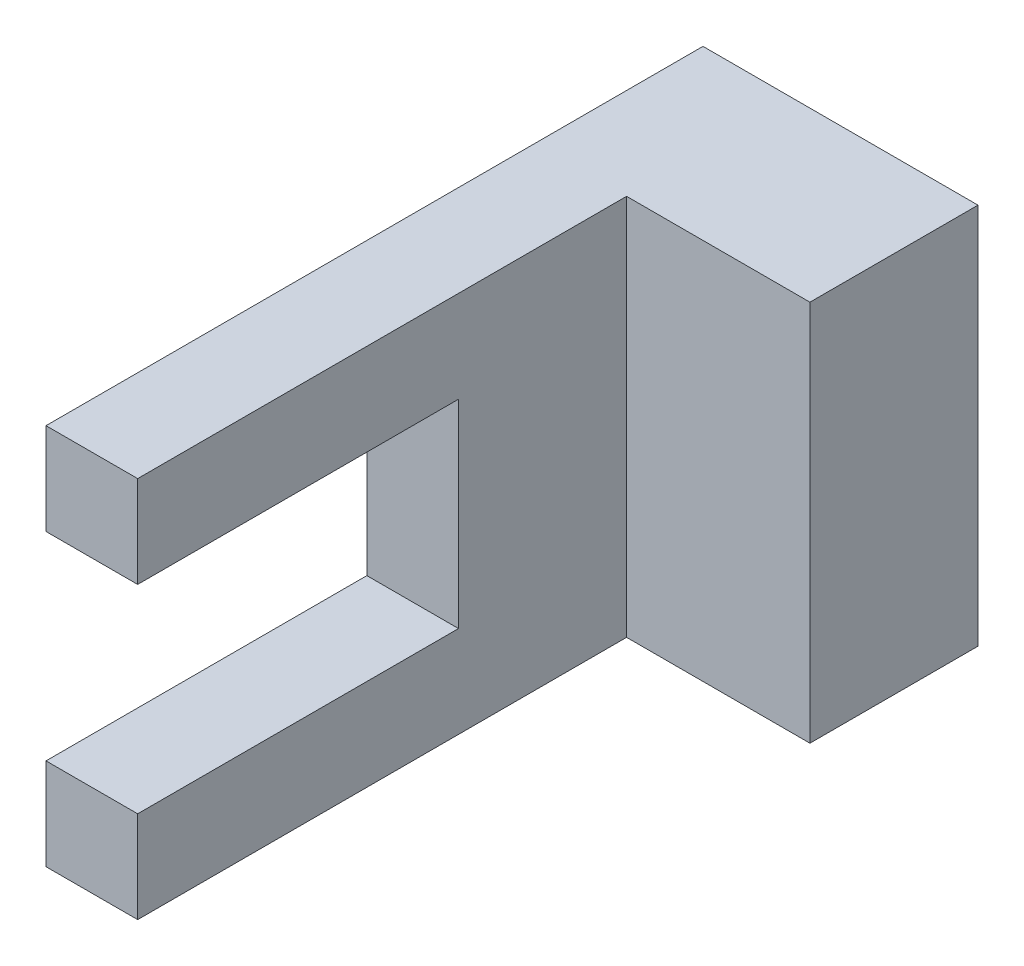
SolidWorks part; units mm, degrees
ref_plane "Front Plane" through (0, 0, 0) normal (0, 0, 1) x (1, 0, 0)
ref_plane "Top Plane" through (0, 0, 0) normal (0, 1, 0) x (1, 0, 0)
ref_plane "Right Plane" through (0, 0, 0) normal (1, 0, 0) x (0, 0, -1)
sketch "Sketch1" plane through (0, 0, 0) normal (1, 0, 0) x (0, 0, -1)
  line L0 (23.5903, 13.6477) -> (-19.4097, 13.6477)
  line L1 (-19.4097, 13.6477) -> (-19.4097, 7.6477)
  line L2 (-19.4097, 7.6477) -> (1.5903, 7.6477)
  line L3 (1.5903, 7.6477) -> (1.5903, -5.3523)
  line L4 (1.5903, -5.3523) -> (-19.4097, -5.3523)
  line L5 (-19.4097, -5.3523) -> (-19.4097, -11.3523)
  line L6 (-19.4097, -11.3523) -> (23.5903, -11.3523)
  line L7 (23.5903, -11.3523) -> (23.5903, 13.6477)
  dimension "D1" = 6
  dimension "D2" = 6
  dimension "D3" = 21
  dimension "D4" = 21
  dimension "D5" = 25
  dimension "D6" = 43
extrude "Boss-Extrude1" add sketch "Sketch1" along normal blind 18
sketch "Sketch2" plane through (0, 0, 19.4097) normal (0, 0, 1) x (1, 0, 0)
  line L0 (18, -11.3523) -> (0, -11.3523) construction
  line L1 (18, 13.6477) -> (6, 13.6477)
  line L2 (18, 13.6477) -> (18, -11.3523)
  line L3 (18, -11.3523) -> (6, -11.3523)
  line L4 (6, 13.6477) -> (6, -11.3523)
  dimension "D1" = 6
extrude "Cut-Extrude1" cut sketch "Sketch2" against normal blind 32
